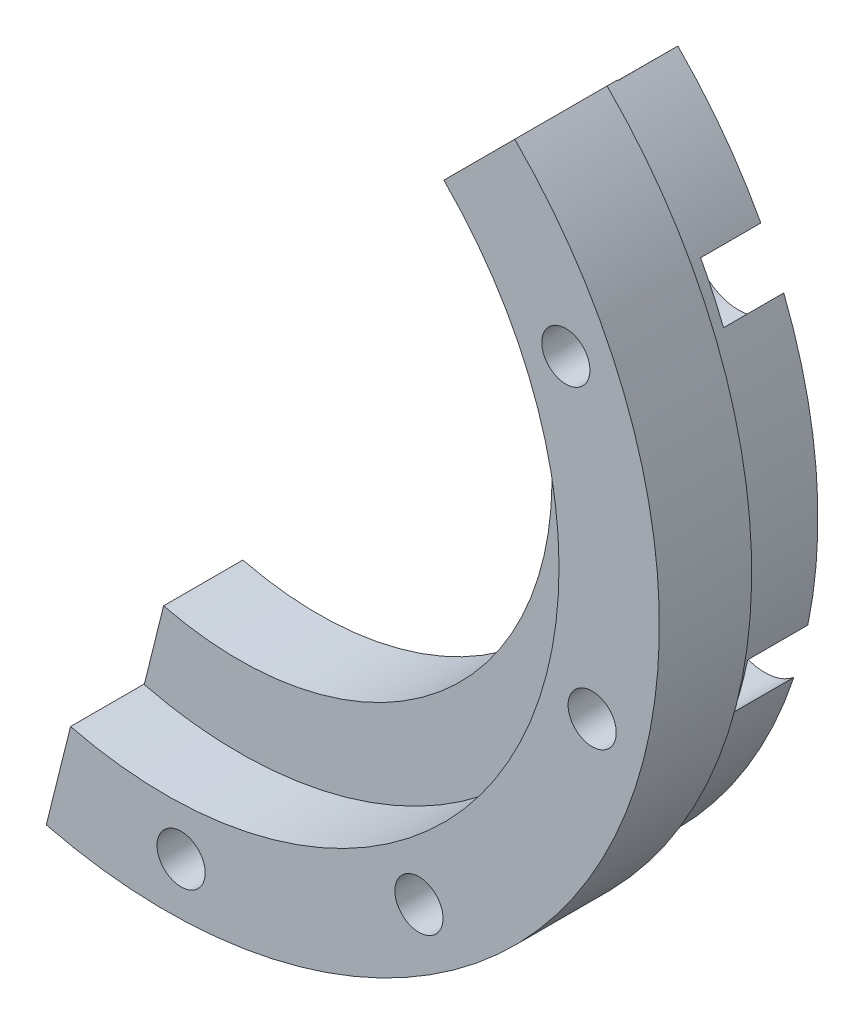
SolidWorks part; units mm, degrees
ref_plane "Front Plane" through (0, 0, 0) normal (0, 0, 1) x (1, 0, 0)
ref_plane "Top Plane" through (0, 0, 0) normal (0, 1, 0) x (1, 0, 0)
ref_plane "Right Plane" through (0, 0, 0) normal (1, 0, 0) x (0, 0, -1)
ref_plane "PZ_p24_600" through (0, 0, 24.6) normal (0, 0, 1) x (1, 0, 0)
sketch "S_prism1" plane through (0, 0, 24.6) normal (0, 0, 1) x (1, 0, 0)
  line L0 (-5.9513, -23.8693) -> (-4.7417, -19.0178)
  line L1 (13.8593, 13.8593) -> (17.3948, 17.3948)
  arc A0 (17.3948, 17.3948) -> (-5.9513, -23.8693) centre (0, 0) cw
  arc A1 (-4.7417, -19.0178) -> (13.8593, 13.8593) centre (0, 0) ccw
extrude "Boss_1" add sketch "S_prism1" along normal blind 5.6
ref_plane "PZ_p21_600" through (0, 0, 21.6) normal (0, 0, 1) x (1, 0, 0)
sketch "S_prism2" plane through (0, 0, 21.6) normal (0, 0, 1) x (1, 0, 0)
  line L0 (-5.7536, -23.1971) -> (-3.7555, -15.1412)
  line L1 (11.0443, 11.0174) -> (16.9205, 16.8792)
  arc A0 (16.9205, 16.8792) -> (-5.7536, -23.1971) centre (0, 0) cw
  arc A1 (-3.7555, -15.1412) -> (11.0443, 11.0174) centre (0, 0) ccw
extrude "Boss_2" add sketch "S_prism2" along normal blind 4.95
ref_plane "PZ_p24_500" through (0, 0, 24.5) normal (0, 0, 1) x (1, 0, 0)
sketch "S_pcut3" plane through (0, 0, 24.5) normal (0, 0, 1) x (1, 0, 0)
  line L0 (-6.4187, -23.955) -> (-6.1858, -23.0856)
  line L1 (16.6023, 17.1922) -> (17.2275, 17.8396)
  arc A0 (17.2275, 17.8396) -> (-6.4187, -23.955) centre (0, 0) cw
  arc A1 (-6.1858, -23.0856) -> (16.6023, 17.1922) centre (0, 0) ccw
extrude "Cut_3" cut sketch "S_pcut3" along normal blind 1.1
ref_plane "PZ_p21_500" through (0, 0, 21.5) normal (0, 0, 1) x (1, 0, 0)
sketch "S_pcut4" plane through (0, 0, 21.5) normal (0, 0, 1) x (1, 0, 0)
  line L0 (-4.3999, -16.4207) -> (-4.0117, -14.9719)
  line L1 (10.7672, 11.1498) -> (11.8092, 12.2288)
  arc A0 (11.8092, 12.2288) -> (-4.3999, -16.4207) centre (0, 0) cw
  arc A1 (-4.0117, -14.9719) -> (10.7672, 11.1498) centre (0, 0) ccw
extrude "Cut_4" cut sketch "S_pcut4" along normal blind 1.1
sketch "S_hole5" plane through (0, 0, 21.5) normal (0, 0, 1) x (1, 0, 0)
  circle A0 centre (19.9388, 9.2976) radius 1.2
  dimension "D1_S_hole5" = 2.4
  dimension "P2" = 19.9388
  dimension "P3" = 9.2976
extrude "Hole_5" cut sketch "S_hole5" along normal blind 8.8
sketch "S_hole6" plane through (0, 0, 21.5) normal (0, 0, 1) x (1, 0, 0)
  circle A0 centre (19.9388, 9.2976) radius 2.3
  dimension "D1_S_hole6" = 4.6
  dimension "P2" = 19.9388
  dimension "P3" = 9.2976
extrude "Hole_6" cut sketch "S_hole6" along normal blind 3.1
sketch "S_hole7" plane through (0, 0, 21.5) normal (0, 0, 1) x (1, 0, 0)
  circle A0 centre (21.2504, -5.694) radius 1.2
  dimension "D1_S_hole7" = 2.4
  dimension "P2" = 21.2504
  dimension "P3" = 5.694
extrude "Hole_7" cut sketch "S_hole7" along normal blind 8.8
sketch "S_hole8" plane through (0, 0, 21.5) normal (0, 0, 1) x (1, 0, 0)
  circle A0 centre (21.2504, -5.694) radius 2.3
  dimension "D1_S_hole8" = 4.6
  dimension "P2" = 21.2504
  dimension "P3" = 5.694
extrude "Hole_8" cut sketch "S_hole8" along normal blind 3.1
sketch "S_hole9" plane through (0, 0, 21.5) normal (0, 0, 1) x (1, 0, 0)
  circle A0 centre (12.6187, -18.0213) radius 1.2
  dimension "D1_S_hole9" = 2.4
  dimension "P2" = 12.6187
  dimension "P3" = 18.0213
extrude "Hole_9" cut sketch "S_hole9" along normal blind 8.8
sketch "S_hole10" plane through (0, 0, 21.5) normal (0, 0, 1) x (1, 0, 0)
  circle A0 centre (12.6187, -18.0213) radius 2.3
  dimension "D1_S_hole10" = 4.6
  dimension "P2" = 12.6187
  dimension "P3" = 18.0213
extrude "Hole_10" cut sketch "S_hole10" along normal blind 3.1
sketch "S_hole11" plane through (0, 0, 21.5) normal (0, 0, 1) x (1, 0, 0)
  circle A0 centre (0.7678, -21.9866) radius 1.2
  dimension "D1_S_hole11" = 2.4
  dimension "P2" = 0.7678
  dimension "P3" = 21.9866
extrude "Hole_11" cut sketch "S_hole11" along normal blind 8.8
sketch "S_hole12" plane through (0, 0, 21.5) normal (0, 0, 1) x (1, 0, 0)
  circle A0 centre (0.7678, -21.9866) radius 2.3
  dimension "D1_S_hole12" = 4.6
  dimension "P2" = 0.7678
  dimension "P3" = 21.9866
extrude "Hole_12" cut sketch "S_hole12" along normal blind 3.1
equation "\"plate_t\" = 3"
equation "\"clearance\" = 0.5"
